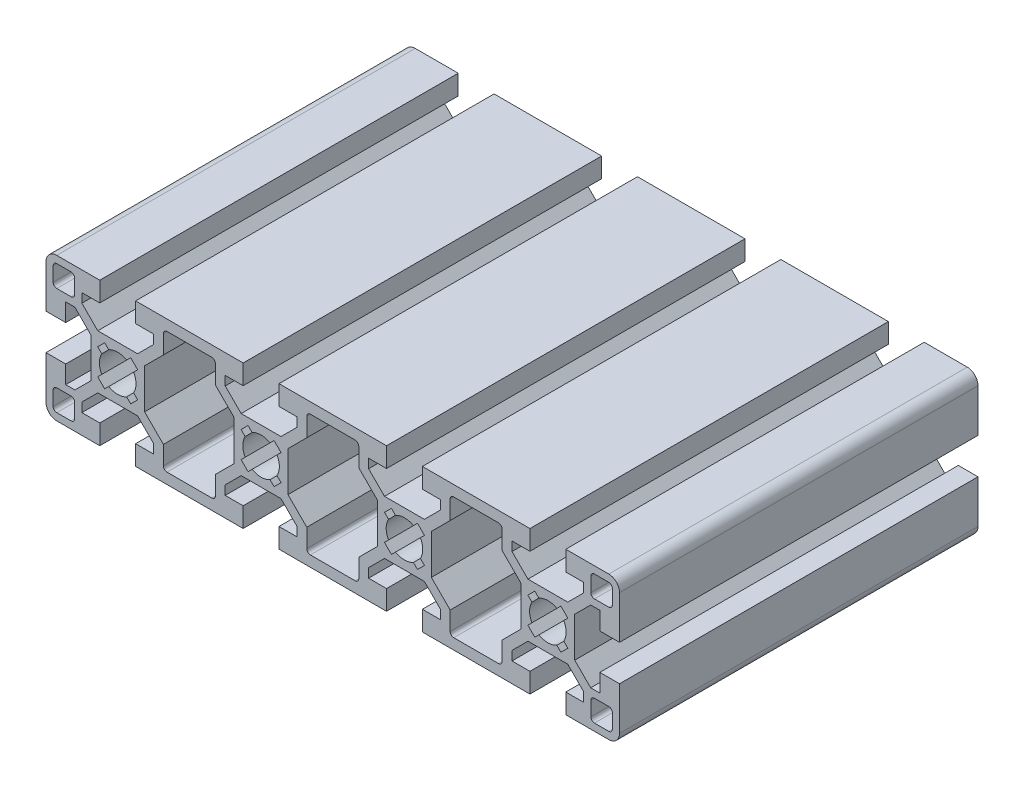
SolidWorks part; units mm, degrees
material "Aluminium"
ref_plane "Front Plane" through (0, 0, 0) normal (0, 0, 1) x (1, 0, 0)
ref_plane "Top Plane" through (0, 0, 0) normal (0, 1, 0) x (1, 0, 0)
ref_plane "Right Plane" through (0, 0, 0) normal (1, 0, 0) x (0, 0, -1)
sketch "Sketch1" plane through (0, 0, 0) normal (0, 0, 1) x (1, 0, 0)
  line L0 (-78, 13) -> (-78, 17)
  line L1 (-77, 18) -> (-73, 18)
  line L2 (-72, 17) -> (-72, 13)
  line L3 (-73, 12) -> (-77, 12)
  line L4 (-55.555, -2.5004) -> (-54.4237, -3.6318)
  line L5 (-54.4237, -3.6318) -> (-56.3682, -5.5763)
  line L6 (-56.3682, -5.5763) -> (-57.4996, -4.445)
  line L7 (-62.5004, -4.445) -> (-63.6318, -5.5763)
  line L8 (-63.6318, -5.5763) -> (-65.5763, -3.6318)
  line L9 (-65.5763, -3.6318) -> (-64.445, -2.5004)
  line L10 (-64.445, 2.5004) -> (-65.5763, 3.6318)
  line L11 (-65.5763, 3.6318) -> (-63.6318, 5.5763)
  line L12 (-63.6318, 5.5763) -> (-62.5004, 4.445)
  line L13 (-57.4996, 4.445) -> (-56.3682, 5.5763)
  line L14 (-56.3682, 5.5763) -> (-54.4237, 3.6318)
  line L15 (-54.4237, 3.6318) -> (-55.555, 2.5004)
  line L16 (-78, -17) -> (-78, -13)
  line L17 (-77, -12) -> (-73, -12)
  line L18 (-72, -13) -> (-72, -17)
  line L19 (-73, -18) -> (-77, -18)
  line L20 (-27.5, 5.5555) -> (-27.5, -5.5555)
  line L21 (-27.5, -5.5555) -> (-32.75, -10.8055)
  line L22 (-32.75, -10.8055) -> (-32.75, -16)
  line L23 (-33.75, -17) -> (-46.25, -17)
  line L24 (-47.25, -16) -> (-47.25, -10.8055)
  line L25 (-47.25, -10.8055) -> (-52.5, -5.5555)
  line L26 (-52.5, -5.5555) -> (-52.5, 5.5555)
  line L27 (-52.5, 5.5555) -> (-47.25, 10.8055)
  line L28 (-47.25, 10.8055) -> (-47.25, 16)
  line L29 (-46.25, 17) -> (-33.75, 17)
  line L30 (-32.75, 16) -> (-32.75, 10.8055)
  line L31 (-32.75, 10.8055) -> (-27.5, 5.5555)
  line L32 (-15.555, -2.5004) -> (-14.4237, -3.6318)
  line L33 (-14.4237, -3.6318) -> (-16.3682, -5.5763)
  line L34 (-16.3682, -5.5763) -> (-17.4996, -4.445)
  line L35 (-22.5004, -4.445) -> (-23.6318, -5.5763)
  line L36 (-23.6318, -5.5763) -> (-25.5763, -3.6318)
  line L37 (-25.5763, -3.6318) -> (-24.445, -2.5004)
  line L38 (-24.445, 2.5004) -> (-25.5763, 3.6318)
  line L39 (-25.5763, 3.6318) -> (-23.6318, 5.5763)
  line L40 (-23.6318, 5.5763) -> (-22.5004, 4.445)
  line L41 (-17.4996, 4.445) -> (-16.3682, 5.5763)
  line L42 (-16.3682, 5.5763) -> (-14.4237, 3.6318)
  line L43 (-14.4237, 3.6318) -> (-15.555, 2.5004)
  line L44 (15.555, 2.5004) -> (14.4237, 3.6318)
  line L45 (14.4237, 3.6318) -> (16.3682, 5.5763)
  line L46 (16.3682, 5.5763) -> (17.4996, 4.445)
  line L47 (22.5004, 4.445) -> (23.6318, 5.5763)
  line L48 (23.6318, 5.5763) -> (25.5763, 3.6318)
  line L49 (25.5763, 3.6318) -> (24.445, 2.5004)
  line L50 (24.445, -2.5004) -> (25.5763, -3.6318)
  line L51 (25.5763, -3.6318) -> (23.6318, -5.5763)
  line L52 (23.6318, -5.5763) -> (22.5004, -4.445)
  line L53 (17.4996, -4.445) -> (16.3682, -5.5763)
  line L54 (16.3682, -5.5763) -> (14.4237, -3.6318)
  line L55 (14.4237, -3.6318) -> (15.555, -2.5004)
  line L56 (27.5, -5.5555) -> (27.5, 5.5555)
  line L57 (27.5, 5.5555) -> (32.75, 10.8055)
  line L58 (32.75, 10.8055) -> (32.75, 16)
  line L59 (33.75, 17) -> (46.25, 17)
  line L60 (47.25, 16) -> (47.25, 10.8055)
  line L61 (47.25, 10.8055) -> (52.5, 5.5555)
  line L62 (52.5, 5.5555) -> (52.5, -5.5555)
  line L63 (52.5, -5.5555) -> (47.25, -10.8055)
  line L64 (47.25, -10.8055) -> (47.25, -16)
  line L65 (46.25, -17) -> (33.75, -17)
  line L66 (32.75, -16) -> (32.75, -10.8055)
  line L67 (32.75, -10.8055) -> (27.5, -5.5555)
  line L68 (78, -13) -> (78, -17)
  line L69 (77, -18) -> (73, -18)
  line L70 (72, -17) -> (72, -13)
  line L71 (73, -12) -> (77, -12)
  line L72 (55.555, 2.5004) -> (54.4237, 3.6318)
  line L73 (54.4237, 3.6318) -> (56.3682, 5.5763)
  line L74 (56.3682, 5.5763) -> (57.4996, 4.445)
  line L75 (62.5004, 4.445) -> (63.6318, 5.5763)
  line L76 (63.6318, 5.5763) -> (65.5763, 3.6318)
  line L77 (65.5763, 3.6318) -> (64.445, 2.5004)
  line L78 (64.445, -2.5004) -> (65.5763, -3.6318)
  line L79 (65.5763, -3.6318) -> (63.6318, -5.5763)
  line L80 (63.6318, -5.5763) -> (62.5004, -4.445)
  line L81 (57.4996, -4.445) -> (56.3682, -5.5763)
  line L82 (56.3682, -5.5763) -> (54.4237, -3.6318)
  line L83 (54.4237, -3.6318) -> (55.555, -2.5004)
  line L84 (78, 17) -> (78, 13)
  line L85 (77, 12) -> (73, 12)
  line L86 (72, 13) -> (72, 17)
  line L87 (73, 18) -> (77, 18)
  line L88 (6.25, -17) -> (-6.25, -17)
  line L89 (-7.25, -16) -> (-7.25, -10.8055)
  line L90 (-7.25, -10.8055) -> (-12.5, -5.5555)
  line L91 (-12.5, -5.5555) -> (-12.5, 5.5555)
  line L92 (-12.5, 5.5555) -> (-7.25, 10.8055)
  line L93 (-7.25, 10.8055) -> (-7.25, 16)
  line L94 (-6.25, 17) -> (6.25, 17)
  line L95 (7.25, 16) -> (7.25, 10.8055)
  line L96 (7.25, 10.8055) -> (12.5, 5.5555)
  line L97 (12.5, 5.5555) -> (12.5, -5.5555)
  line L98 (12.5, -5.5555) -> (7.25, -10.8055)
  line L99 (7.25, -10.8055) -> (7.25, -16)
  line L100 (-15, -20) -> (15, -20)
  line L101 (15, -20) -> (15, -14.5)
  line L102 (15, -14.5) -> (10, -14.5)
  line L103 (10, -14.5) -> (10, -11.9445)
  line L104 (10, -11.9445) -> (14.4445, -7.5)
  line L105 (14.4445, -7.5) -> (25.5555, -7.5)
  line L106 (25.5555, -7.5) -> (30, -11.9445)
  line L107 (30, -11.9445) -> (30, -14.5)
  line L108 (30, -14.5) -> (25, -14.5)
  line L109 (25, -14.5) -> (25, -20)
  line L110 (25, -20) -> (55, -20)
  line L111 (55, -20) -> (55, -14.5)
  line L112 (55, -14.5) -> (50, -14.5)
  line L113 (50, -14.5) -> (50, -11.9445)
  line L114 (50, -11.9445) -> (54.4445, -7.5)
  line L115 (54.4445, -7.5) -> (65.5555, -7.5)
  line L116 (65.5555, -7.5) -> (70, -11.9445)
  line L117 (70, -11.9445) -> (70, -14.5)
  line L118 (70, -14.5) -> (65, -14.5)
  line L119 (65, -14.5) -> (65, -20)
  line L120 (65, -20) -> (77, -20)
  line L121 (80, -17) -> (80, -5)
  line L122 (80, -5) -> (74.5, -5)
  line L123 (74.5, -5) -> (74.5, -10)
  line L124 (74.5, -10) -> (71.9445, -10)
  line L125 (71.9445, -10) -> (67.5, -5.5555)
  line L126 (67.5, -5.5555) -> (67.5, 5.5555)
  line L127 (67.5, 5.5555) -> (71.9445, 10)
  line L128 (71.9445, 10) -> (74.5, 10)
  line L129 (74.5, 10) -> (74.5, 5)
  line L130 (74.5, 5) -> (80, 5)
  line L131 (80, 5) -> (80, 17)
  line L132 (77, 20) -> (65, 20)
  line L133 (65, 20) -> (65, 14.5)
  line L134 (65, 14.5) -> (70, 14.5)
  line L135 (70, 14.5) -> (70, 11.9445)
  line L136 (70, 11.9445) -> (65.5555, 7.5)
  line L137 (65.5555, 7.5) -> (54.4445, 7.5)
  line L138 (54.4445, 7.5) -> (50, 11.9445)
  line L139 (50, 11.9445) -> (50, 14.5)
  line L140 (50, 14.5) -> (55, 14.5)
  line L141 (55, 14.5) -> (55, 20)
  line L142 (55, 20) -> (25, 20)
  line L143 (25, 20) -> (25, 14.5)
  line L144 (25, 14.5) -> (30, 14.5)
  line L145 (30, 14.5) -> (30, 11.9445)
  line L146 (30, 11.9445) -> (25.5555, 7.5)
  line L147 (25.5555, 7.5) -> (14.4445, 7.5)
  line L148 (14.4445, 7.5) -> (10, 11.9445)
  line L149 (10, 11.9445) -> (10, 14.5)
  line L150 (10, 14.5) -> (15, 14.5)
  line L151 (15, 14.5) -> (15, 20)
  line L152 (15, 20) -> (-15, 20)
  line L153 (-15, 20) -> (-15, 14.5)
  line L154 (-15, 14.5) -> (-10, 14.5)
  line L155 (-10, 14.5) -> (-10, 11.9445)
  line L156 (-10, 11.9445) -> (-14.4445, 7.5)
  line L157 (-14.4445, 7.5) -> (-25.5555, 7.5)
  line L158 (-25.5555, 7.5) -> (-30, 11.9445)
  line L159 (-30, 11.9445) -> (-30, 14.5)
  line L160 (-30, 14.5) -> (-25, 14.5)
  line L161 (-25, 14.5) -> (-25, 20)
  line L162 (-25, 20) -> (-55, 20)
  line L163 (-55, 20) -> (-55, 14.5)
  line L164 (-55, 14.5) -> (-50, 14.5)
  line L165 (-50, 14.5) -> (-50, 11.9445)
  line L166 (-50, 11.9445) -> (-54.4445, 7.5)
  line L167 (-54.4445, 7.5) -> (-65.5555, 7.5)
  line L168 (-65.5555, 7.5) -> (-70, 11.9445)
  line L169 (-70, 11.9445) -> (-70, 14.5)
  line L170 (-70, 14.5) -> (-65, 14.5)
  line L171 (-65, 14.5) -> (-65, 20)
  line L172 (-65, 20) -> (-77, 20)
  line L173 (-80, 17) -> (-80, 5)
  line L174 (-80, 5) -> (-74.5, 5)
  line L175 (-74.5, 5) -> (-74.5, 10)
  line L176 (-74.5, 10) -> (-71.9445, 10)
  line L177 (-71.9445, 10) -> (-67.5, 5.5555)
  line L178 (-67.5, 5.5555) -> (-67.5, -5.5555)
  line L179 (-67.5, -5.5555) -> (-71.9445, -10)
  line L180 (-71.9445, -10) -> (-74.5, -10)
  line L181 (-74.5, -10) -> (-74.5, -5)
  line L182 (-74.5, -5) -> (-80, -5)
  line L183 (-80, -5) -> (-80, -17)
  line L184 (-77, -20) -> (-65, -20)
  line L185 (-65, -20) -> (-65, -14.5)
  line L186 (-65, -14.5) -> (-70, -14.5)
  line L187 (-70, -14.5) -> (-70, -11.9445)
  line L188 (-70, -11.9445) -> (-65.5555, -7.5)
  line L189 (-65.5555, -7.5) -> (-54.4445, -7.5)
  line L190 (-54.4445, -7.5) -> (-50, -11.9445)
  line L191 (-50, -11.9445) -> (-50, -14.5)
  line L192 (-50, -14.5) -> (-55, -14.5)
  line L193 (-55, -14.5) -> (-55, -20)
  line L194 (-55, -20) -> (-25, -20)
  line L195 (-25, -20) -> (-25, -14.5)
  line L196 (-25, -14.5) -> (-30, -14.5)
  line L197 (-30, -14.5) -> (-30, -11.9445)
  line L198 (-30, -11.9445) -> (-25.5555, -7.5)
  line L199 (-25.5555, -7.5) -> (-14.4445, -7.5)
  line L200 (-14.4445, -7.5) -> (-10, -11.9445)
  line L201 (-10, -11.9445) -> (-10, -14.5)
  line L202 (-10, -14.5) -> (-15, -14.5)
  line L203 (-15, -14.5) -> (-15, -20)
  arc A0 (-78, 17) -> (-77, 18) centre (-77, 17) cw
  arc A1 (-73, 18) -> (-72, 17) centre (-73, 17) cw
  arc A2 (-72, 13) -> (-73, 12) centre (-73, 13) cw
  arc A3 (-77, 12) -> (-78, 13) centre (-77, 13) cw
  arc A4 (-55.555, 2.5004) -> (-55.555, -2.5004) centre (-60, 0) cw
  arc A5 (-57.4996, -4.445) -> (-62.5004, -4.445) centre (-60, 0) cw
  arc A6 (-64.445, -2.5004) -> (-64.445, 2.5004) centre (-60, 0) cw
  arc A7 (-62.5004, 4.445) -> (-57.4996, 4.445) centre (-60, 0) cw
  arc A8 (-78, -13) -> (-77, -12) centre (-77, -13) cw
  arc A9 (-73, -12) -> (-72, -13) centre (-73, -13) cw
  arc A10 (-72, -17) -> (-73, -18) centre (-73, -17) cw
  arc A11 (-77, -18) -> (-78, -17) centre (-77, -17) cw
  arc A12 (-32.75, -16) -> (-33.75, -17) centre (-33.75, -16) cw
  arc A13 (-46.25, -17) -> (-47.25, -16) centre (-46.25, -16) cw
  arc A14 (-47.25, 16) -> (-46.25, 17) centre (-46.25, 16) cw
  arc A15 (-33.75, 17) -> (-32.75, 16) centre (-33.75, 16) cw
  arc A16 (-15.555, 2.5004) -> (-15.555, -2.5004) centre (-20, 0) cw
  arc A17 (-17.4996, -4.445) -> (-22.5004, -4.445) centre (-20, 0) cw
  arc A18 (-24.445, -2.5004) -> (-24.445, 2.5004) centre (-20, 0) cw
  arc A19 (-22.5004, 4.445) -> (-17.4996, 4.445) centre (-20, 0) cw
  arc A20 (15.555, -2.5004) -> (15.555, 2.5004) centre (20, 0) cw
  arc A21 (17.4996, 4.445) -> (22.5004, 4.445) centre (20, 0) cw
  arc A22 (24.445, 2.5004) -> (24.445, -2.5004) centre (20, 0) cw
  arc A23 (22.5004, -4.445) -> (17.4996, -4.445) centre (20, 0) cw
  arc A24 (32.75, 16) -> (33.75, 17) centre (33.75, 16) cw
  arc A25 (46.25, 17) -> (47.25, 16) centre (46.25, 16) cw
  arc A26 (47.25, -16) -> (46.25, -17) centre (46.25, -16) cw
  arc A27 (33.75, -17) -> (32.75, -16) centre (33.75, -16) cw
  arc A28 (78, -17) -> (77, -18) centre (77, -17) cw
  arc A29 (73, -18) -> (72, -17) centre (73, -17) cw
  arc A30 (72, -13) -> (73, -12) centre (73, -13) cw
  arc A31 (77, -12) -> (78, -13) centre (77, -13) cw
  arc A32 (55.555, -2.5004) -> (55.555, 2.5004) centre (60, 0) cw
  arc A33 (57.4996, 4.445) -> (62.5004, 4.445) centre (60, 0) cw
  arc A34 (64.445, 2.5004) -> (64.445, -2.5004) centre (60, 0) cw
  arc A35 (62.5004, -4.445) -> (57.4996, -4.445) centre (60, 0) cw
  arc A36 (78, 13) -> (77, 12) centre (77, 13) cw
  arc A37 (73, 12) -> (72, 13) centre (73, 13) cw
  arc A38 (72, 17) -> (73, 18) centre (73, 17) cw
  arc A39 (77, 18) -> (78, 17) centre (77, 17) cw
  arc A40 (-6.25, -17) -> (-7.25, -16) centre (-6.25, -16) cw
  arc A41 (-7.25, 16) -> (-6.25, 17) centre (-6.25, 16) cw
  arc A42 (6.25, 17) -> (7.25, 16) centre (6.25, 16) cw
  arc A43 (7.25, -16) -> (6.25, -17) centre (6.25, -16) cw
  arc A44 (77, -20) -> (80, -17) centre (77, -17) ccw
  arc A45 (80, 17) -> (77, 20) centre (77, 17) ccw
  arc A46 (-77, 20) -> (-80, 17) centre (-77, 17) ccw
  arc A47 (-80, -17) -> (-77, -20) centre (-77, -17) ccw
extrude "Boss-Extrude1" add sketch "Sketch1" against normal mid plane 100
